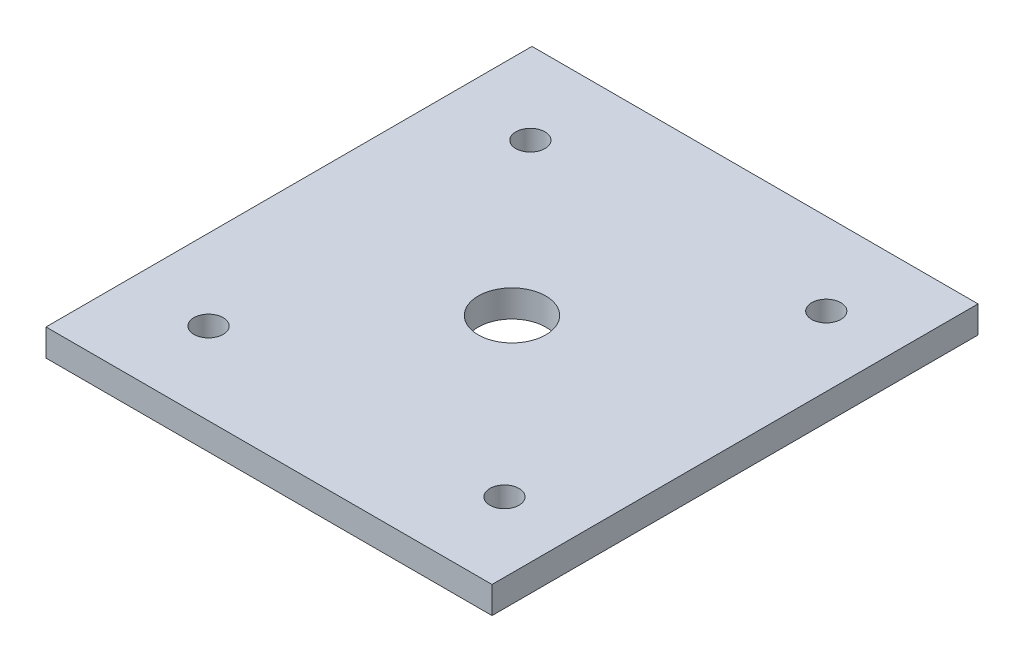
SolidWorks part; units mm, degrees
material "6061 Alloy"
ref_plane "Front Plane" through (0, 0, 0) normal (0, 0, 1) x (1, 0, 0)
ref_plane "Top Plane" through (0, 0, 0) normal (0, 1, 0) x (1, 0, 0)
ref_plane "Right Plane" through (0, 0, 0) normal (1, 0, 0) x (0, 0, -1)
sketch "Sketch1" plane through (0, 0, 0) normal (0, 1, 0) x (1, 0, 0)
  line L1 (-52.451, 57.15) -> (52.451, 57.15)
  line L2 (-52.451, 57.15) -> (-52.451, -57.15)
  line L3 (-52.451, -57.15) -> (52.451, -57.15)
  line L4 (52.451, 57.15) -> (52.451, -57.15)
  line L5 (-52.451, 57.15) -> (52.451, -57.15) construction
  line L6 (-52.451, -57.15) -> (52.451, 57.15) construction
  point P0 (0, 0)
  dimension "D1" = 114.3
  dimension "D2" = 104.902
extrude "Boss-Extrude1" add sketch "Sketch1" along normal blind 6.35
sketch "Sketch3" plane through (0, 0, 0) normal (0, -1, 0) x (1, 0, 0)
  line L0 (1.27, 0) -> (1.27, -20.7585) construction
  line L1 (0, 0) -> (-13.1006, 0) construction
  line L2 (-52.451, -57.15) -> (-52.451, 57.15) construction
  line L3 (-52.451, 57.15) -> (52.451, 57.15) construction
  line L4 (52.451, -57.15) -> (-52.451, -57.15) construction
  line L6 (52.451, 57.15) -> (52.451, -57.15) construction
  circle A0 centre (-33.528, 37.846) radius 3.429
  circle A1 centre (-33.528, -37.846) radius 3.429
  circle A2 centre (36.068, 37.846) radius 3.429
  circle A3 centre (36.068, -37.846) radius 3.429
  dimension "D1" = 18.923
  dimension "D4" = 16.383
  dimension "D2" = 19.304
  dimension "D3" = 19.304
extrude "Cut-Extrude2" cut sketch "Sketch3" against normal up to next
sketch "Sketch4" plane through (0, 0, 0) normal (0, -1, 0) x (1, 0, 0)
  circle A0 centre (0, 0) radius 7.9375
extrude "Cut-Extrude3" cut sketch "Sketch4" against normal up to next
